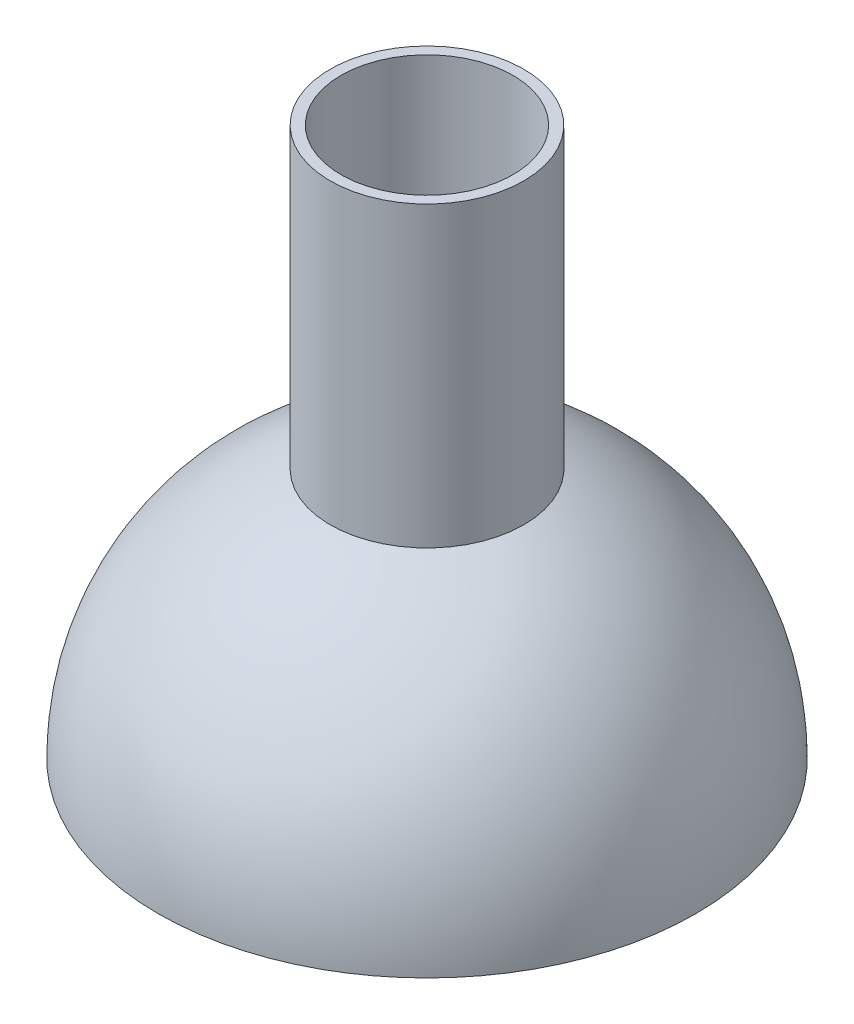
SolidWorks part; units mm, degrees
ref_plane "Front Plane" through (0, 0, 0) normal (0, 0, 1) x (1, 0, 0)
ref_plane "Top Plane" through (0, 0, 0) normal (0, 1, 0) x (1, 0, 0)
ref_plane "Right Plane" through (0, 0, 0) normal (1, 0, 0) x (0, 0, -1)
sketch "Sketch1" plane through (0, 0, 0) normal (0, 1, 0) x (1, 0, 0)
  line L0 (0, 25) -> (0, -25)
  arc A0 (0, -25) -> (0, 25) centre (0, 0) ccw
  dimension "D1" = 50
revolve "Revolve1" add sketch "Sketch1" angle 180 about L0
sketch "Sketch2" plane through (0, 0, 0) normal (0, -1, 0) x (1, 0, 0)
  line L0 (0, -20) -> (0, 20)
  circle A2 centre (0, 0) radius 20
  arc A3 (0, -20) -> (0, 20) centre (0, 0) ccw
  dimension "D1" = 5
revolve "Cut-Revolve1" cut sketch "Sketch2" angle 180 about L0
sketch "Sketch6" plane through (0, 0, 0) normal (0, -1, 0) x (-1, 0, 0)
  circle A0 centre (0, 0) radius 9
extrude "Boss-Extrude1" add sketch "Sketch6" against normal blind 30 from offset 21 separate body offset against normal yes
sketch "Sketch7" plane through (0, 51, 0) normal (0, 1, 0) x (-1, 0, 0)
  circle A0 centre (0, 0) radius 8
extrude "Cut-Extrude6" cut sketch "Sketch7" against normal blind 35
